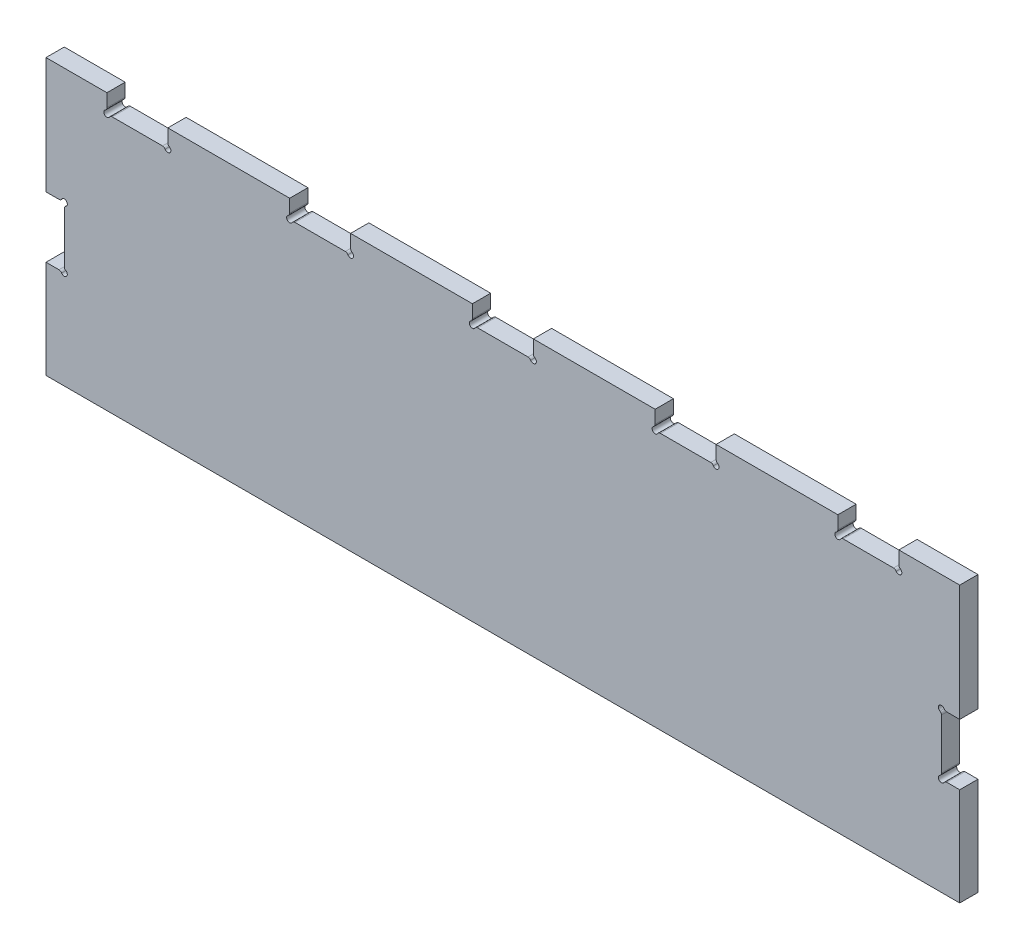
SolidWorks part; units mm, degrees
ref_plane "Front Plane" through (0, 0, 0) normal (0, 0, 1) x (1, 0, 0)
ref_plane "Top Plane" through (0, 0, 0) normal (0, 1, 0) x (1, 0, 0)
ref_plane "Right Plane" through (0, 0, 0) normal (1, 0, 0) x (0, 0, -1)
sketch "Sketch1" plane through (0, 0, 0) normal (0, 0, 1) x (1, 0, 0)
  line L2 (65, -3) -> (65, 0)
  line L4 (55, -3) -> (55, 0)
  line L6 (35, -3) -> (35, 0)
  line L8 (25, -3) -> (25, 0)
  line L10 (5, -3) -> (5, 0)
  line L12 (-5, -3) -> (-5, 0)
  line L14 (-25, -3) -> (-25, 0)
  line L16 (-35, -3) -> (-35, 0)
  line L18 (-55, -3) -> (-55, 0)
  line L20 (-65, -3) -> (-65, 0)
  line L22 (-75, -45.2) -> (75, -45.2)
  line L28 (0, 0) -> (0, -60.0812) construction
  line L36 (-65, 0) -> (-75, 0)
  line L39 (-65, -3) -> (-55, -3)
  line L40 (-55, 0) -> (-35, 0)
  line L41 (-35, -3) -> (-25, -3)
  line L42 (-25, 0) -> (-5, 0)
  line L43 (-5, -3) -> (5, -3)
  line L44 (5, 0) -> (25, 0)
  line L45 (25, -3) -> (35, -3)
  line L46 (35, 0) -> (55, 0)
  line L47 (55, -3) -> (65, -3)
  line L48 (65, 0) -> (75, 0)
  line L49 (-75, -45.2) -> (-75, -24.1) construction
  line L51 (-75, -24.1) -> (-72, -24.1) construction
  line L53 (-72, -29.1) -> (-72, -19.1)
  line L55 (-72, -29.1) -> (-75, -29.1)
  line L57 (-72, -19.1) -> (-75, -19.1)
  line L59 (-75, 0) -> (-75, -19.1)
  line L60 (-75, -29.1) -> (-75, -45.2)
  line L61 (75, -29.1) -> (75, -45.2)
  line L62 (72, -29.1) -> (75, -29.1)
  line L63 (72, -29.1) -> (72, -19.1)
  line L64 (72, -19.1) -> (75, -19.1)
  line L65 (75, 0) -> (75, -19.1)
  point P29 (-72, -24.1)
  dimension "D3" = 150
  dimension "D4" = 10
  dimension "D5" = 20
  dimension "D6" = 10
  dimension "D7" = 20
  dimension "D8" = 10
  dimension "D9" = 20
  dimension "D10" = 10
  dimension "D11" = 20
  dimension "D12" = 10
  dimension "D14" = 10
  dimension "D15" = 45.2
  dimension "D16" = 3
  dimension "D17" = 3
  dimension "D18" = 3
  dimension "D19" = 3
  dimension "D20" = 3
  dimension "D21" = 3
  dimension "D22" = 3
  dimension "D23" = 3
  dimension "D24" = 3
  dimension "D26" = 21.1
  dimension "D27" = 3
  dimension "D28" = 10
  dimension "D29" = 3
extrude "Boss-Extrude1" add sketch "Sketch1" along normal mid plane 3
sketch "Sketch2" plane through (0, 0, 1.5) normal (0, 0, 1) x (1, 0, 0)
  circle A0 centre (-72, -29.1) radius 0.5
  circle A1 centre (-72, -19.1) radius 0.5
  circle A2 centre (-65, -3) radius 0.5
  circle A3 centre (-55, -3) radius 0.5
  circle A4 centre (-35, -3) radius 0.5
  circle A5 centre (-25, -3) radius 0.5
  circle A6 centre (-5, -3) radius 0.5
  circle A7 centre (5, -3) radius 0.5
  circle A8 centre (25, -3) radius 0.5
  circle A9 centre (35, -3) radius 0.5
  circle A10 centre (55, -3) radius 0.5
  circle A11 centre (65, -3) radius 0.5
  circle A12 centre (72, -19.1) radius 0.5
  circle A13 centre (72, -29.1) radius 0.5
  dimension "D1" = 1
extrude "Cut-Extrude1" cut sketch "Sketch2" against normal through all and the other way through all
fillet "Fillet1" radius 0.5 28 edges at (72.5, -29.1, 0) (72, -28.6, 0) (72, -19.6, 0) (72.5, -19.1, 0) (65, -2.5, 0) (64.5, -3, 0) (55.5, -3, 0) (55, -2.5, 0) (35, -2.5, 0) (34.5, -3, 0) (25, -2.5, 0) (25.5, -3, 0) (5, -2.5, 0) (4.5, -3, 0) (-5, -2.5, 0) (-4.5, -3, 0) (-25, -2.5, 0) (-25.5, -3, 0) (-34.5, -3, 0) (-35, -2.5, 0) (-55, -2.5, 0) (-55.5, -3, 0) (-64.5, -3, 0) (-65, -2.5, 0) (-72.5, -19.1, 0) (-72.5, -29.1, 0) (-72, -28.6, 0) (-72, -19.6, 0)
